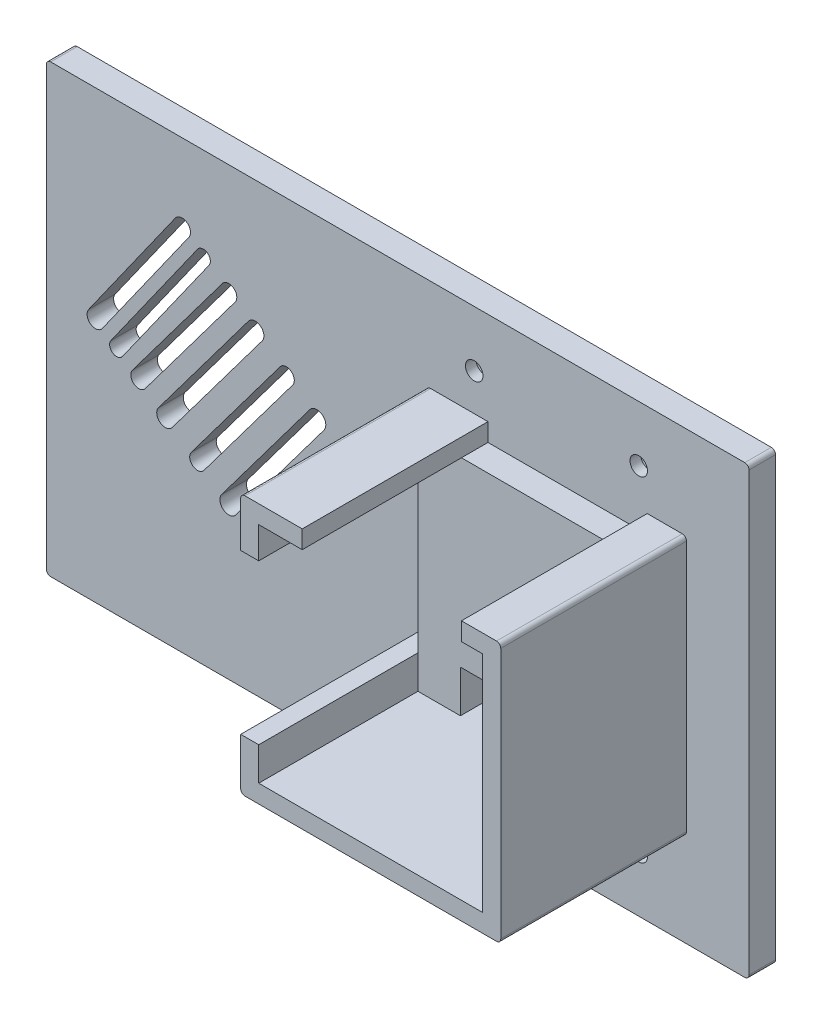
SolidWorks part; units mm, degrees
ref_plane "前视基准面" through (0, 0, 0) normal (0, 0, 1) x (1, 0, 0)
ref_plane "上视基准面" through (0, 0, 0) normal (0, 1, 0) x (1, 0, 0)
ref_plane "右视基准面" through (0, 0, 0) normal (1, 0, 0) x (0, 0, -1)
sketch "草图1" plane through (0, 0, 0) normal (0, 0, 1) x (1, 0, 0)
  line L1 (-75, 42) -> (75, 42)
  line L2 (-75, 42) -> (-75, -42)
  line L3 (-75, -42) -> (75, -42)
  line L4 (75, 42) -> (75, -42)
  line L5 (-75, 42) -> (75, -42) construction
  line L6 (-75, -42) -> (75, 42) construction
  point P0 (0, 0)
  dimension "D1" = 150
  dimension "D2" = 84
extrude "凸台-拉伸1" add sketch "草图1" along normal blind 5
sketch "草图2" plane through (0, 0, 5) normal (0, 0, 1) x (1, 0, 0)
  line L0 (0, 0) -> (0, 21.1)
  line L1 (0, 21.1) -> (42.2, 21.1)
  line L2 (42.2, 21.1) -> (42.2, -21.1)
  line L3 (42.2, -21.1) -> (0, -21.1)
  line L4 (0, -21.1) -> (0, 0)
  line L6 (21.1, 21.1) -> (21.1, -21.1) construction
  line L8 (-3.4, 24.5) -> (45.6, 24.5)
  line L9 (-3.4, 24.5) -> (-3.4, -24.5)
  line L10 (-3.4, -24.5) -> (45.6, -24.5)
  line L11 (45.6, 24.5) -> (45.6, -24.5)
  line L12 (-3.4, 24.5) -> (45.6, -24.5) construction
  line L13 (-3.4, -24.5) -> (45.6, 24.5) construction
  point P9 (21.1, 0)
  point P10 (21.1, 21.1)
  dimension "D1" = 42.2
  dimension "D2" = 42.2
  dimension "D3" = 49
  dimension "D4" = 49
extrude "凸台-拉伸2" add sketch "草图2" along normal blind 35
sketch "草图3" plane through (-3.4, 0, 0) normal (-1, 0, 0) x (0, 0, 1)
  line L0 (5, 24.5) -> (5, 15.1805) construction
  line L1 (5, 24.5) -> (5, -24.5) construction
  line L2 (5, -24.5) -> (5, -14.8195) construction
  line L3 (5, 42) -> (5, -42) construction
  line L4 (5, 15.1805) -> (40, 15.1805)
  line L5 (40, 24.5) -> (40, -24.5) construction
  line L6 (40, 15.1805) -> (40, -14.8195)
  line L7 (40, -14.8195) -> (5, -14.8195)
  line L8 (5, -14.8195) -> (5, 15.1805)
  dimension "D1" = 30
extrude "切除-拉伸1" cut sketch "草图3" against normal blind 21
sketch "草图4" plane through (0, 24.5, 0) normal (0, 1, 0) x (1, 0, 0)
  line L0 (-3.4, -5) -> (8.1947, -5) construction
  line L1 (75, -5) -> (-75, -5) construction
  line L2 (45.6, -5) -> (38.1947, -5) construction
  line L3 (45.6, -5) -> (-3.4, -5) construction
  line L4 (8.1947, -5) -> (8.1947, -40)
  line L5 (45.6, -40) -> (-3.4, -40) construction
  line L6 (8.1947, -40) -> (38.1947, -40)
  line L7 (38.1947, -40) -> (38.1947, -5)
  line L8 (38.1947, -5) -> (8.1947, -5)
  dimension "D1" = 30
extrude "切除-拉伸2" cut sketch "草图4" against normal blind 21
fillet "圆角1" radius 0.8 8 edges at (75, 42, 2.5) (75, -42, 2.5) (-75, -42, 2.5) (-75, 42, 2.5) (-3.4, 24.5, 22.5) (45.6, 24.5, 22.5) (45.6, -24.5, 22.5) (-3.4, -24.5, 22.5)
sketch "草图5" plane through (0, 0, 5) normal (0, 0, 1) x (1, 0, 0)
  line L0 (-49.437, 27.3401) -> (-65.7662, 4.2696) construction
  line L1 (-48.1492, 26.4287) -> (-64.4784, 3.3581)
  line L2 (-50.7248, 28.2516) -> (-67.054, 5.181)
  line L3 (-45.4414, 24.5121) -> (-61.7706, 1.4415) construction
  line L4 (-44.3604, 23.747) -> (-60.6896, 0.6764)
  line L5 (-46.5225, 25.2773) -> (-62.8516, 2.2067)
  line L6 (-40.6396, 21.1134) -> (-57.6016, -1.5093) construction
  line L7 (-39.4344, 20.2098) -> (-56.3963, -2.4129)
  line L8 (-41.8448, 22.0171) -> (-58.8068, -0.6056)
  line L9 (-35.6436, 17.3675) -> (-52.6056, -5.2552) construction
  line L10 (-34.3524, 16.3994) -> (-51.3143, -6.2233)
  line L11 (-36.9348, 18.3357) -> (-53.8968, -4.287)
  line L12 (-29.7875, 12.9768) -> (-46.5225, -9.343) construction
  line L13 (-28.5991, 12.0857) -> (-45.334, -10.2341)
  line L14 (-30.976, 13.8679) -> (-47.7109, -8.4519)
  line L15 (-24.0412, 8.6683) -> (-40.6396, -13.4695) construction
  line L16 (-22.7019, 7.6641) -> (-39.3003, -14.4737)
  line L17 (-25.3805, 9.6725) -> (-41.9789, -12.4653)
  arc A0 (-48.1492, 26.4287) -> (-50.7248, 28.2516) centre (-49.437, 27.3401) ccw
  arc A1 (-67.054, 5.181) -> (-64.4784, 3.3581) centre (-65.7662, 4.2696) ccw
  arc A2 (-44.3604, 23.747) -> (-46.5225, 25.2773) centre (-45.4414, 24.5121) ccw
  arc A3 (-62.8516, 2.2067) -> (-60.6896, 0.6764) centre (-61.7706, 1.4415) ccw
  arc A4 (-39.4344, 20.2098) -> (-41.8448, 22.0171) centre (-40.6396, 21.1134) ccw
  arc A5 (-58.8068, -0.6056) -> (-56.3963, -2.4129) centre (-57.6016, -1.5093) ccw
  arc A6 (-34.3524, 16.3994) -> (-36.9348, 18.3357) centre (-35.6436, 17.3675) ccw
  arc A7 (-53.8968, -4.287) -> (-51.3143, -6.2233) centre (-52.6056, -5.2552) ccw
  arc A8 (-28.5991, 12.0857) -> (-30.976, 13.8679) centre (-29.7875, 12.9768) ccw
  arc A9 (-47.7109, -8.4519) -> (-45.334, -10.2341) centre (-46.5225, -9.343) ccw
  arc A10 (-22.7019, 7.6641) -> (-25.3805, 9.6725) centre (-24.0412, 8.6683) ccw
  arc A11 (-41.9789, -12.4653) -> (-39.3003, -14.4737) centre (-40.6396, -13.4695) ccw
  point P2 (-57.6016, 15.8049)
  point P7 (-53.606, 12.9768)
  point P14 (-49.1206, 9.8021)
  point P21 (-44.1246, 6.0562)
  point P28 (-38.155, 1.8169)
  point P35 (-32.3404, -2.4006)
extrude "切除-拉伸3" cut sketch "草图5" against normal blind 21
sketch "草图6" plane through (0, 0, 5) normal (0, 0, 1) x (1, 0, 0)
  line L0 (57.3769, 42) -> (57.3769, -42)
  line L1 (74.2, 42) -> (-74.2, 42) construction
  line L2 (-74.2, -42) -> (74.2, -42) construction
  line L3 (57.3769, -42) -> (84.7919, -42)
  line L5 (84.7919, 42) -> (57.3769, 42)
  line L6 (84.7919, 42) -> (84.7919, -42)
extrude "切除-拉伸4" cut sketch "草图6" against normal blind 21
fillet "圆角2" radius 0.8 2 edges at (57.3769, 42, 2.5) (57.3769, -42, 2.5)
sketch "草图10" plane through (0, 0, 5) normal (0, 0, 1) x (1, 0, 0)
  line L0 (0, -21.1) -> (8, -21.1) construction
  line L1 (0, -21.1) -> (42.2, -21.1) construction
  line L2 (8, -21.1) -> (8, -13.15) construction
  line L3 (42.2, -21.1) -> (34.3, -21.1) construction
  line L4 (0, -21.1) -> (42.2, -21.1) construction
  line L5 (34.3, -21.1) -> (34.3, -13.15) construction
  line L6 (34.3, -13.15) -> (8, -13.15) construction
  line L7 (0, 21.1) -> (0, -21.1)
  line L8 (0, -21.1) -> (8, -21.1)
  line L9 (8, -21.1) -> (8, -13.15)
  line L10 (8, -13.15) -> (34.3, -13.15)
  line L11 (34.3, -13.15) -> (34.3, -21.1)
  line L12 (34.3, -21.1) -> (42.2, -21.1)
  line L13 (42.2, -21.1) -> (42.2, 21.1)
  line L14 (42.2, 21.1) -> (0, 21.1)
extrude "凸台-拉伸5" add sketch "草图10" along normal blind 5
sketch "草图12" plane through (0, 0, 5) normal (0, 0, 1) x (1, 0, 0)
  line L0 (0, -21.1) -> (42.2, -21.1) construction
  line L1 (21.1, -21.1) -> (21.1, -42) construction
  line L2 (-74.2, -42) -> (56.5769, -42) construction
  line L3 (21.1, -24.5) -> (21.1, -31.5) construction
  line L4 (-2.6, -24.5) -> (44.8, -24.5) construction
  line L5 (21.1, -31.5) -> (5.6, -31.5) construction
  line L6 (0, 0) -> (57.3769, 0) construction
  line L7 (57.3769, 41.2) -> (57.3769, -41.2) construction
  circle A0 centre (5.6, -31.5) radius 1.65
  circle A1 centre (5.6, 31.5) radius 1.65
  circle A2 centre (36.6, -31.5) radius 1.65
  circle A3 centre (36.6, 31.5) radius 1.65
  dimension "D2" = 3.3
  dimension "D1" = 15.5
  dimension "D3" = 7
extrude "切除-拉伸5" cut sketch "草图12" against normal blind 10
sketch "草图13" plane through (0, 0, 0) normal (0, 0, -1) x (-1, 0, 0)
  line L0 (-36.6, 31.5) -> (-5.6, 31.5) construction
  line L1 (-21.1, 31.5) -> (-21.1, -28.6231) construction
  circle A0 centre (-5.6, 31.5) radius 3
  circle A1 centre (-5.6, -31.5) radius 3
  circle A2 centre (-36.6, -31.5) radius 3
  circle A3 centre (-36.6, 31.5) radius 3
  dimension "D1" = 6
  dimension "D2" = 6
extrude "切除-拉伸6" cut sketch "草图13" against normal blind 3
